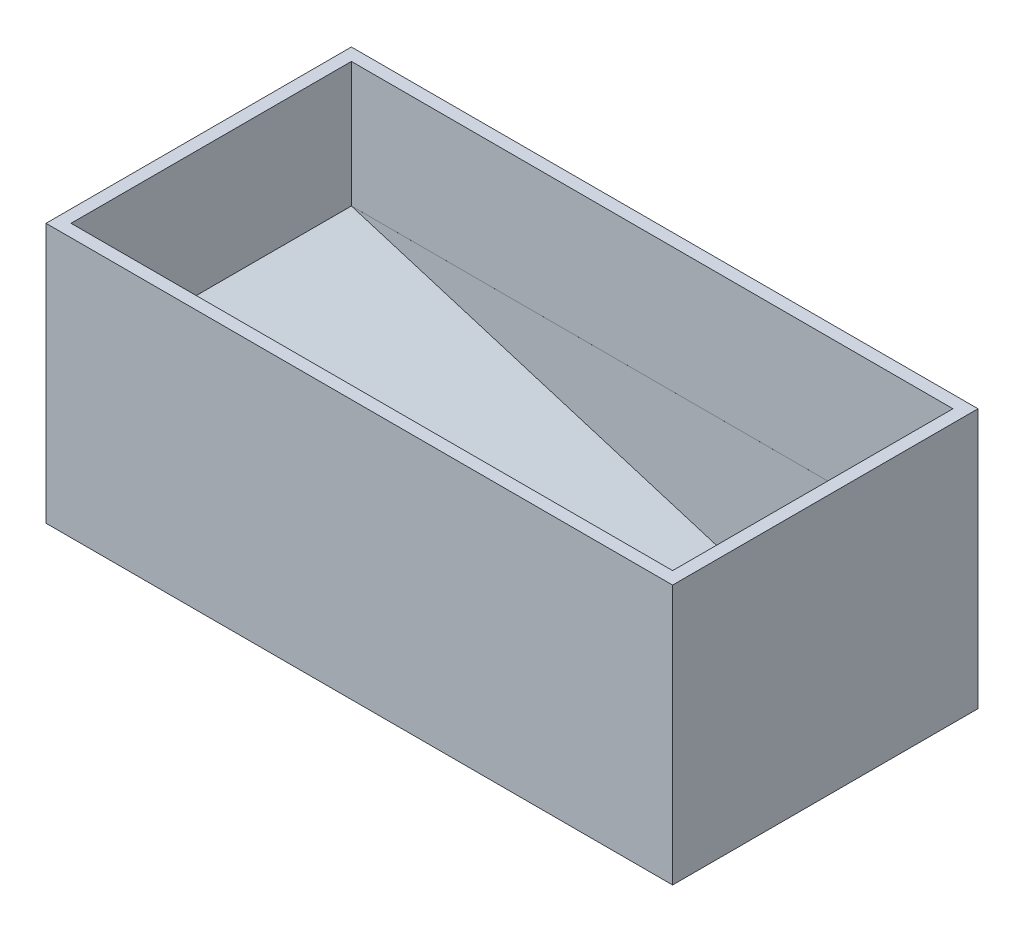
SolidWorks part; units mm, degrees
ref_plane "Front Plane" through (0, 0, 0) normal (0, 0, 1) x (1, 0, 0)
ref_plane "Top Plane" through (0, 0, 0) normal (0, 1, 0) x (1, 0, 0)
ref_plane "Right Plane" through (0, 0, 0) normal (1, 0, 0) x (0, 0, -1)
sketch "Sketch1" plane through (0, 0, 0) normal (0, 1, 0) x (1, 0, 0)
  line L1 (0, 0) -> (200.21, 0)
  line L2 (0, 0) -> (0, 97.58)
  line L3 (0, 97.58) -> (200.21, 97.58)
  line L4 (200.21, 0) -> (200.21, 97.58)
  dimension "D1" = 200.21
  dimension "D2" = 97.58
extrude "Boss-Extrude1" add sketch "Sketch1" along normal blind 43
sketch "Sketch2" plane through (0, 43, 0) normal (0, 1, 0) x (1, 0, 0)
  line L0 (200.21, 97.58) -> (200.21, 49.98) construction
  line L1 (200.21, 0) -> (200.21, 97.58) construction
  line L2 (200.21, 49.98) -> (165.7, 49.98) construction
  circle A0 centre (165.7, 49.98) radius 30.26
extrude "Cut-Extrude1" cut sketch "Sketch2" against normal blind 43
sketch "Sketch3" plane through (0, 43, 0) normal (0, 1, 0) x (1, 0, 0)
  line L0 (165.7, 49.98) -> (135.44, 49.98) construction
  line L1 (135.44, 49.98) -> (131.19, 49.98) construction
  line L2 (131.19, 0) -> (131.19, 4) construction
  line L3 (0, 0) -> (200.21, 0) construction
  line L5 (131.19, 4) -> (135.19, 4) construction
  line L7 (200.21, 97.58) -> (200.21, 93.58) construction
  line L8 (200.21, 0) -> (200.21, 97.58) construction
  line L9 (200.21, 93.58) -> (196.21, 93.58) construction
  line L11 (135.19, 4) -> (196.21, 4)
  line L12 (135.19, 4) -> (135.19, 93.58)
  line L13 (135.19, 93.58) -> (196.21, 93.58)
  line L14 (196.21, 4) -> (196.21, 93.58)
  circle A0 centre (165.7, 49.98) radius 30.26 construction
extrude "Cut-Extrude4" cut sketch "Sketch3" against normal blind 40
sketch "Sketch6" plane through (0, 43, 0) normal (0, 1, 0) x (1, 0, 0)
  line L0 (0, 0) -> (0, 4) construction
  line L1 (0, 97.58) -> (0, 0) construction
  line L2 (0, 4) -> (4, 4) construction
  line L4 (4, 4) -> (135.19, 4)
  line L5 (4, 4) -> (4, 93.58)
  line L6 (4, 93.58) -> (135.19, 93.58)
  line L7 (135.19, 4) -> (135.19, 93.58)
  dimension "D1" = 131.19
extrude "Cut-Extrude6" cut sketch "Sketch6" against normal blind 40
sketch "Sketch9" plane through (0, 0, -93.58) normal (0, 0, 1) x (1, 0, 0)
  line L0 (4, 3) -> (135.19, 3)
  line L1 (196.21, 3) -> (4, 3) construction
  line L2 (135.19, 3) -> (4, 43)
  line L3 (4, 43) -> (4, 3)
extrude "Boss-Extrude2" add sketch "Sketch9" along normal blind 92
sketch "Sketch10" plane through (0, 43, 0) normal (0, 1, 0) x (1, 0, 0)
  line L0 (0, 97.58) -> (0, 0) construction
  line L1 (200.21, 0) -> (0, 0)
  line L2 (200.21, 0) -> (200.21, 4.0049)
  line L3 (200.21, 4.0049) -> (0, 4.0049)
  line L4 (0, 0) -> (0, 4.0049)
extrude "Boss-Extrude3" add sketch "Sketch10" along normal blind 40
sketch "Sketch11" plane through (0, 43, 0) normal (0, 1, 0) x (1, 0, 0)
  line L0 (200.21, 97.58) -> (0, 97.58) construction
  line L1 (0, 4.0049) -> (3.9979, 4.0049)
  line L2 (0, 4.0049) -> (0, 97.58)
  line L3 (0, 97.58) -> (3.9979, 97.58)
  line L4 (3.9979, 4.0049) -> (3.9979, 97.58)
extrude "Boss-Extrude4" add sketch "Sketch11" along normal blind 40
sketch "Sketch14" plane through (0, 43, 0) normal (0, 1, 0) x (1, 0, 0)
  line L1 (200.21, 97.58) -> (1.9838, 97.58)
  line L2 (200.21, 97.58) -> (200.21, 93.582)
  line L3 (200.21, 93.582) -> (1.9838, 93.582)
  line L4 (1.9838, 97.58) -> (1.9838, 93.582)
extrude "Boss-Extrude8" add sketch "Sketch14" along normal blind 40
sketch "Sketch15" plane through (0, 43, 0) normal (0, 1, 0) x (1, 0, 0)
  line L1 (200.21, 4.0049) -> (196.2093, 4.0049)
  line L2 (200.21, 4.0049) -> (200.21, 94.6808)
  line L3 (200.21, 94.6808) -> (196.2093, 94.6808)
  line L4 (196.2093, 4.0049) -> (196.2093, 94.6808)
extrude "Boss-Extrude9" add sketch "Sketch15" along normal blind 40
sketch "Sketch16" plane through (0, 0, -97.58) normal (0, 0, -1) x (-1, 0, 0)
  line L0 (0, 0) -> (-127.19, 0)
  line L1 (-200.21, 0) -> (0, 0) construction
  line L2 (0, 0) -> (0, 40)
  line L3 (0, 83) -> (0, 0) construction
  line L4 (0, 40) -> (-127.19, 0)
extrude "Cut-Extrude7" cut sketch "Sketch16" against normal blind 93.53
sketch "Sketch17" plane through (11.4474, 36.3999, 0) normal (-0.3, -0.9539, 0) x (0.9539, -0.3, 0)
  line L0 (-12.0002, -97.58) -> (-12.0002, -93.58) construction
  line L1 (-12.0002, -4.05) -> (-12.0002, -97.58) construction
  line L3 (-12.0002, -93.58) -> (121.3314, -93.58)
  line L4 (-12.0002, -93.58) -> (-12.0002, -97.58)
  line L5 (-12.0002, -97.58) -> (121.3314, -97.58)
  line L6 (121.3314, -93.58) -> (121.3314, -97.58)
extrude "Boss-Extrude10" add sketch "Sketch17" along normal blind 45
sketch "Sketch18" plane through (0, 0, -97.58) normal (0, 0, -1) x (-1, 0, 0)
  line L0 (0, 61.5) -> (0, -49938.5) construction
  line L1 (0, 83) -> (0, 40) construction
  line L2 (-142.6022, 0) -> (49857.3978, 0) construction
  line L5 (0, 53.4688) -> (19.9908, 53.4688)
  line L6 (0, 53.4688) -> (0, -14.0136)
  line L7 (0, -14.0136) -> (19.9908, -14.0136)
  line L8 (19.9908, 53.4688) -> (19.9908, -14.0136)
  point P4 (0, 61.5)
extrude "Cut-Extrude8" cut sketch "Sketch18" against normal blind 45
sketch "Sketch19" plane through (0, 0, -97.58) normal (0, 0, -1) x (-1, 0, 0)
  line L0 (-151.1983, 0) -> (49848.8017, 0) construction
  line L3 (-127.19, 0) -> (3.0147, 0)
  line L4 (-127.19, 0) -> (-127.19, -63.1116)
  line L5 (-127.19, -63.1116) -> (3.0147, -63.1116)
  line L6 (3.0147, 0) -> (3.0147, -63.1116)
extrude "Cut-Extrude9" cut sketch "Sketch19" against normal blind 45
sketch "Sketch20" plane through (0, 0, -4.05) normal (0, 0, -1) x (-1, 0, 0)
  line L0 (0, 0) -> (0, 2)
  line L1 (0, 0) -> (0, 40) construction
  line L2 (0, 2) -> (-120.8305, 2)
  line L3 (0, 40) -> (-127.19, 0) construction
  line L4 (-120.8305, 2) -> (-127.19, 0)
  line L5 (-127.19, 0) -> (0, 0)
extrude "Boss-Extrude11" add sketch "Sketch20" along normal blind 10
sketch "Sketch21" plane through (0, 0, -93.58) normal (0, 0, 1) x (1, 0, 0)
  line L0 (0, 0) -> (0, 2)
  line L1 (0, 40) -> (0, 0) construction
  line L2 (0, 2) -> (120.8305, 2)
  line L3 (127.19, 0) -> (0, 40) construction
  line L4 (120.8305, 2) -> (127.19, 0)
  line L5 (127.19, 0) -> (0, 0)
extrude "Boss-Extrude12" add sketch "Sketch21" along normal blind 10
